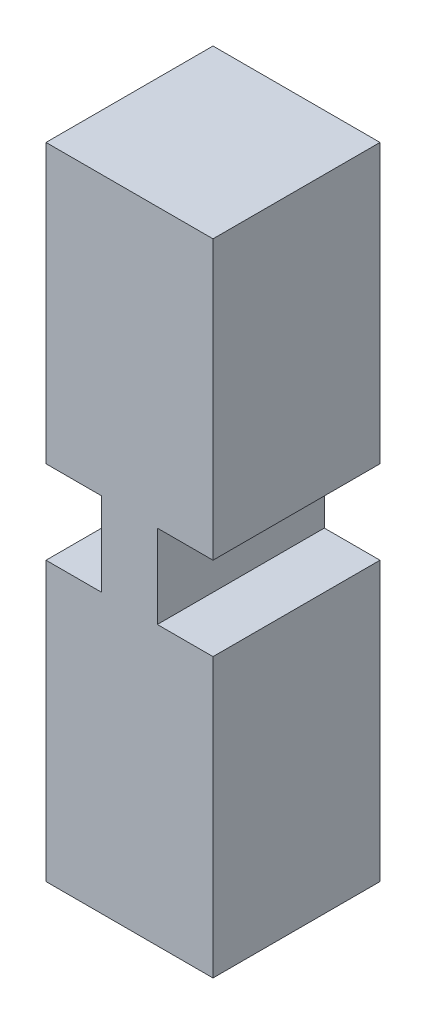
SolidWorks part; units mm, degrees
material "Air"
ref_plane "Front Plane" through (0, 0, 0) normal (0, 0, 1) x (1, 0, 0)
ref_plane "Top Plane" through (0, 0, 0) normal (0, 1, 0) x (1, 0, 0)
ref_plane "Right Plane" through (0, 0, 0) normal (1, 0, 0) x (0, 0, -1)
sketch "Sketch1" plane through (0, 0, 0) normal (0, 0, 1) x (1, 0, 0)
  line L1 (-30, -115) -> (30, -115)
  line L2 (-30, -115) -> (-30, -15)
  line L3 (-30, -15) -> (30, -15)
  line L4 (30, -115) -> (30, -15)
  line L5 (0, -15) -> (0, -115) construction
  line L6 (-30, -65) -> (30, -65) construction
  point P16 (0, -65)
extrude "Boss-Extrude1" add sketch "Sketch1" along normal mid plane 60
sketch "Sketch2" plane through (0, 0, 0) normal (0, 0, 1) x (1, 0, 0)
  line L1 (-30, 15) -> (30, 15)
  line L2 (-30, 15) -> (-30, 115)
  line L3 (-30, 115) -> (30, 115)
  line L4 (30, 15) -> (30, 115)
  line L5 (0, 115) -> (0, 15) construction
  line L6 (-30, 65) -> (30, 65) construction
  point P16 (0, 65)
extrude "Boss-Extrude2" add sketch "Sketch2" along normal mid plane 60
sketch "Sketch3" plane through (0, 0, 0) normal (0, 0, 1) x (1, 0, 0)
  line L0 (30, -15) -> (-30, -15) construction
  line L1 (-10, -15) -> (10, -15)
  line L2 (-10, -15) -> (-10, 15)
  line L3 (-10, 15) -> (10, 15)
  line L4 (10, -15) -> (10, 15)
  line L5 (0, 15) -> (0, -15) construction
  line L6 (-10, 0) -> (10, 0) construction
  line L7 (-30, 15) -> (30, 15) construction
  point P20 (0, 0)
extrude "Boss-Extrude3" add sketch "Sketch3" along normal mid plane 60
sketch "Sketch4" plane through (0, 0, 0) normal (0, 0, 1) x (1, 0, 0)
  line L0 (-10, 15) -> (-10, -15) construction
  line L1 (-11.6, -13.4) -> (-10, -13.4)
  line L2 (-11.6, -13.4) -> (-11.6, -10.4)
  line L3 (-11.6, -10.4) -> (-10, -10.4)
  line L4 (-10, -13.4) -> (-10, -10.4)
  line L5 (-10.8, -10.4) -> (-10.8, -13.4) construction
  line L6 (-11.6, -11.9) -> (-10, -11.9) construction
  point P20 (-10.8, -11.9)
extrude "Boss-Extrude4" add sketch "Sketch4" along normal mid plane 56.8
sketch "Sketch5" plane through (0, 0, 0) normal (0, 0, 1) x (1, 0, 0)
  line L1 (-14.6, -13.4) -> (-11.6, -13.4)
  line L2 (-14.6, -13.4) -> (-14.6, 13.4)
  line L3 (-14.6, 13.4) -> (-11.6, 13.4)
  line L4 (-11.6, -13.4) -> (-11.6, 13.4)
  line L5 (-13.1, 13.4) -> (-13.1, -13.4) construction
  line L6 (-14.6, 0) -> (-11.6, 0) construction
  line L7 (-19.2, 10.4) -> (-14.6, 10.4)
  line L8 (-19.2, 10.4) -> (-19.2, 13.4)
  line L9 (-19.2, 13.4) -> (-14.6, 13.4)
  line L10 (-14.6, 10.4) -> (-14.6, 13.4)
  line L11 (-16.9, 13.4) -> (-16.9, 10.4) construction
  line L12 (-19.2, 11.9) -> (-14.6, 11.9) construction
  line L13 (-19.2, -13.4) -> (-16.9, -13.4)
  line L14 (-19.2, -13.4) -> (-19.2, 13.4)
  line L15 (-19.2, 13.4) -> (-16.9, 13.4)
  line L16 (-16.9, -13.4) -> (-16.9, 13.4)
  line L17 (-18.05, 13.4) -> (-18.05, -13.4) construction
  line L18 (-19.2, 0) -> (-16.9, 0) construction
  line L19 (-23.8, -13.4) -> (-14.6, -13.4)
  line L20 (-23.8, -13.4) -> (-23.8, -10.4)
  line L21 (-23.8, -10.4) -> (-14.6, -10.4)
  line L22 (-14.6, -13.4) -> (-14.6, -10.4)
  line L23 (-19.2, -10.4) -> (-19.2, -13.4) construction
  line L24 (-23.8, -11.9) -> (-14.6, -11.9) construction
  line L25 (-23.8, -13.4) -> (-19.2, -13.4)
  line L26 (-23.8, -13.4) -> (-23.8, 13.4)
  line L27 (-23.8, 13.4) -> (-19.2, 13.4)
  line L28 (-19.2, -13.4) -> (-19.2, 13.4)
  line L29 (-21.5, 13.4) -> (-21.5, -13.4) construction
  line L30 (-23.8, 0) -> (-19.2, 0) construction
  line L31 (-28.4, 10.4) -> (-21.5, 10.4)
  line L32 (-28.4, 10.4) -> (-28.4, 13.4)
  line L33 (-28.4, 13.4) -> (-21.5, 13.4)
  line L34 (-21.5, 10.4) -> (-21.5, 13.4)
  line L35 (-24.95, 13.4) -> (-24.95, 10.4) construction
  line L36 (-28.4, 11.9) -> (-21.5, 11.9) construction
  line L37 (-28.4, -13.4) -> (-24.95, -13.4)
  line L38 (-28.4, -13.4) -> (-28.4, 13.4)
  line L39 (-28.4, 13.4) -> (-24.95, 13.4)
  line L40 (-24.95, -13.4) -> (-24.95, 13.4)
  line L41 (-26.675, 13.4) -> (-26.675, -13.4) construction
  line L42 (-28.4, 0) -> (-24.95, 0) construction
  line L43 (11.6, -13.4) -> (14.6, -13.4)
  line L44 (11.6, -13.4) -> (11.6, 13.4)
  line L45 (11.6, 13.4) -> (14.6, 13.4)
  line L46 (14.6, -13.4) -> (14.6, 13.4)
  line L47 (13.1, 13.4) -> (13.1, -13.4) construction
  line L48 (11.6, 0) -> (14.6, 0) construction
  line L49 (14.6, 10.4) -> (19.2, 10.4)
  line L50 (14.6, 10.4) -> (14.6, 13.4)
  line L51 (14.6, 13.4) -> (19.2, 13.4)
  line L52 (19.2, 10.4) -> (19.2, 13.4)
  line L53 (16.9, 13.4) -> (16.9, 10.4) construction
  line L54 (14.6, 11.9) -> (19.2, 11.9) construction
  line L55 (14.6, -13.4) -> (19.2, -13.4)
  line L56 (14.6, -13.4) -> (14.6, 13.4)
  line L57 (14.6, 13.4) -> (19.2, 13.4)
  line L58 (19.2, -13.4) -> (19.2, 13.4)
  line L59 (16.9, 13.4) -> (16.9, -13.4) construction
  line L60 (14.6, 0) -> (19.2, 0) construction
  line L61 (16.9, -13.4) -> (23.8, -13.4)
  line L62 (16.9, -13.4) -> (16.9, -11.9)
  line L63 (16.9, -11.9) -> (23.8, -11.9)
  line L64 (23.8, -13.4) -> (23.8, -11.9)
  line L65 (20.35, -11.9) -> (20.35, -13.4) construction
  line L66 (16.9, -12.65) -> (23.8, -12.65) construction
  line L67 (20.35, -13.4) -> (23.8, -13.4)
  line L68 (20.35, -13.4) -> (20.35, 11.9)
  line L69 (20.35, 11.9) -> (23.8, 11.9)
  line L70 (23.8, -13.4) -> (23.8, 11.9)
  line L71 (22.075, 11.9) -> (22.075, -13.4) construction
  line L72 (20.35, -0.75) -> (23.8, -0.75) construction
  line L73 (23.8, -13.4) -> (28.4, -13.4)
  line L74 (23.8, -13.4) -> (23.8, 11.9)
  line L75 (23.8, 11.9) -> (28.4, 11.9)
  line L76 (28.4, -13.4) -> (28.4, 11.9)
  line L77 (26.1, 11.9) -> (26.1, -13.4) construction
  line L78 (23.8, -0.75) -> (28.4, -0.75) construction
  point P16 (-13.1, 0)
  point P25 (-16.9, 11.9)
  point P32 (-18.05, 0)
  point P43 (-19.2, -11.9)
  point P46 (-21.5, 0)
  point P54 (-24.95, 11.9)
  point P61 (-26.675, 0)
  point P69 (13.1, 0)
  point P77 (16.9, 11.9)
  point P84 (16.9, 0)
  point P91 (20.35, -12.65)
  point P98 (22.075, -0.75)
  point P105 (26.1, -0.75)
